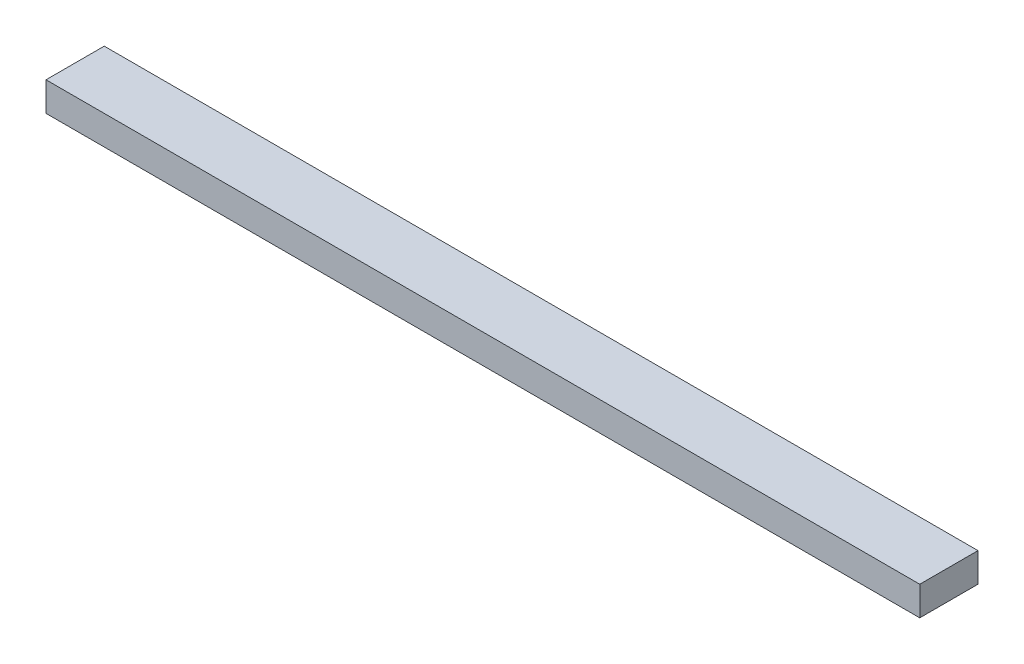
SolidWorks part; units mm, degrees
ref_plane "Front Plane" through (0, 0, 0) normal (0, 0, 1) x (1, 0, 0)
ref_plane "Top Plane" through (0, 0, 0) normal (0, 1, 0) x (1, 0, 0)
ref_plane "Right Plane" through (0, 0, 0) normal (1, 0, 0) x (0, 0, -1)
sketch "Sketch1" plane through (0, 0, 0) normal (0, 1, 0) x (1, 0, 0)
  line L1 (-762, -50.8) -> (762, -50.8)
  line L2 (-762, -50.8) -> (-762, 50.8)
  line L3 (-762, 50.8) -> (762, 50.8)
  line L4 (762, -50.8) -> (762, 50.8)
  line L5 (-762, -50.8) -> (762, 50.8) construction
  line L6 (-762, 50.8) -> (762, -50.8) construction
  point P0 (0, 0)
  dimension "D1" = 101.6
  dimension "D2" = 1524
extrude "Boss-Extrude1" add sketch "Sketch1" along normal blind 50.8
